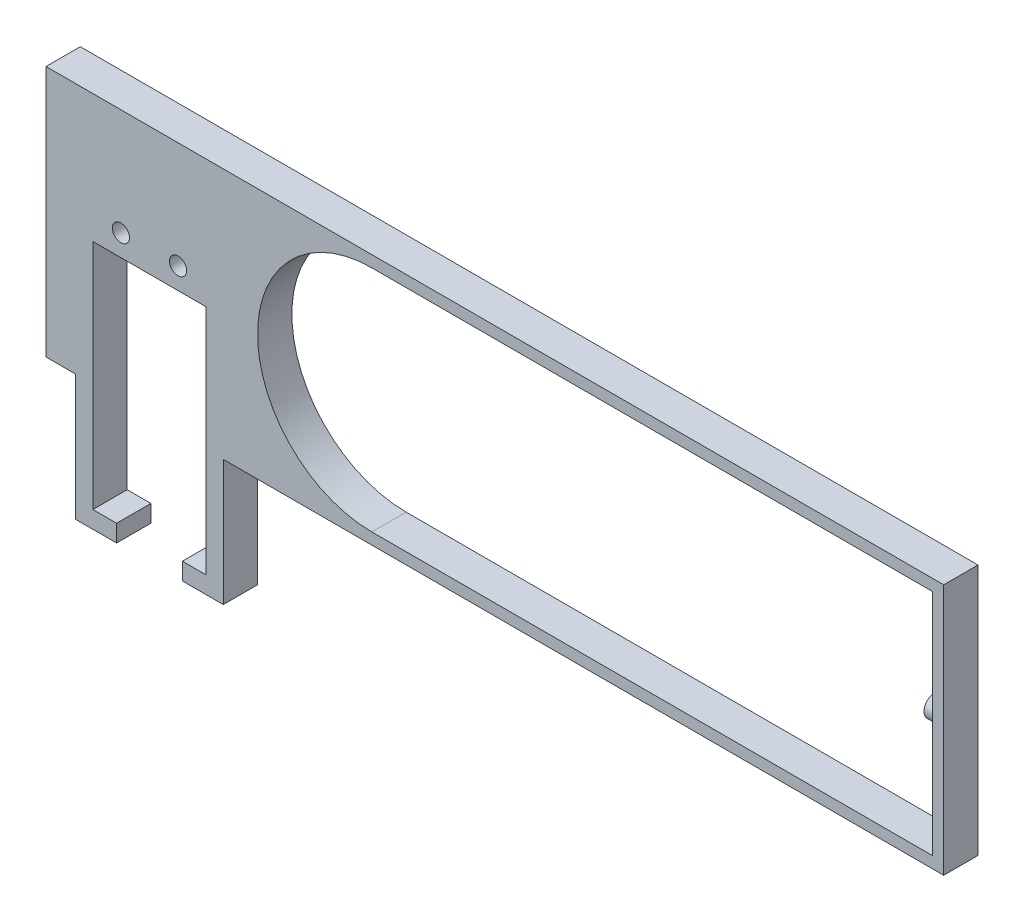
SolidWorks part; units mm, degrees
other "Markup1"
sketch "Sketch3" plane through (63.5, 44, 6) normal (0.035, 0.053, 0.998) x (0.9992, 0.0181, -0.036)
ref_plane "Front Plane" through (0, 0, 0) normal (0, 0, 1) x (1, 0, 0)
ref_plane "Top Plane" through (0, 0, 0) normal (0, 1, 0) x (1, 0, 0)
ref_plane "Right Plane" through (0, 0, 0) normal (1, 0, 0) x (0, 0, -1)
sketch "Sketch1" plane through (0, 0, 0) normal (0, 0, 1) x (1, 0, 0)
  line L3 (0, 0) -> (100, 0)
  line L4 (100, 0) -> (100, 44)
  line L5 (100, 44) -> (0, 44)
  line L6 (0, 44) -> (-57, 44)
  line L7 (-57, 44) -> (-57, 0)
  line L8 (-57, 0) -> (-51.8, 0)
  line L9 (-51.8, 0) -> (-51.8, -22)
  line L10 (-51.8, -22) -> (-44.65, -22)
  line L11 (-44.65, -22) -> (-44.65, -19)
  line L12 (-44.65, -19) -> (-48.8, -19)
  line L13 (-48.8, -19) -> (-48.8, 21.6)
  line L14 (-48.8, 21.6) -> (-29, 21.6)
  line L15 (-29, 21.6) -> (-29, -19)
  line L16 (-29, -19) -> (-33.15, -19)
  line L17 (-33.15, -19) -> (-33.15, -22)
  line L18 (-33.15, -22) -> (-26, -22)
  line L20 (0, 2) -> (98, 2)
  line L21 (98, 2) -> (98, 42)
  line L22 (98, 42) -> (0, 42)
  line L23 (-43.9, 25.353) -> (-33.9, 25.353) construction
  line L24 (0, 0) -> (-26, 0)
  line L25 (-26, 0) -> (-26, -22)
  line L26 (-44.65, -19) -> (-33.15, -19) construction
  circle A1 centre (-43.9, 25.353) radius 1.5
  circle A2 centre (-33.9, 25.353) radius 1.5
  arc A3 (0, 42) -> (0, 2) centre (0, 22) ccw
  point P2 (-38.9, -19)
  point P28 (-38.9, 25.353)
  point P29 (-38.9, 21.6)
  point P30 (-20, 22)
  dimension "D1" = 2
  dimension "D5" = 20
  dimension "D7" = 3
  dimension "D8" = 3
  dimension "D2" = 2
  dimension "D3" = 2
  dimension "D4" = 120
  dimension "D6" = 3.753
  dimension "D9" = 10
  dimension "D10" = 8.2
  dimension "D11" = 40.6
  dimension "D12" = 19.8
  dimension "D13" = 11.5
  dimension "D14" = 3
  dimension "D15" = 3
  dimension "D16" = 3
  dimension "D17" = 22
  dimension "D18" = 37
extrude "Boss-Extrude1" add sketch "Sketch1" along normal blind 6
sketch "Sketch2" plane through (98, 0, 0) normal (-1, 0, 0) x (0, 0, 1)
  line L0 (3, 42) -> (3, 2) construction
  line L1 (6, 42) -> (0, 42) construction
  line L2 (6, 2) -> (0, 2) construction
  circle A0 centre (3, 22) radius 1.905
  point P2 (3, 22)
  dimension "D1" = 3.81
extrude "Boss-Extrude2" add sketch "Sketch2" along normal blind 2.54
